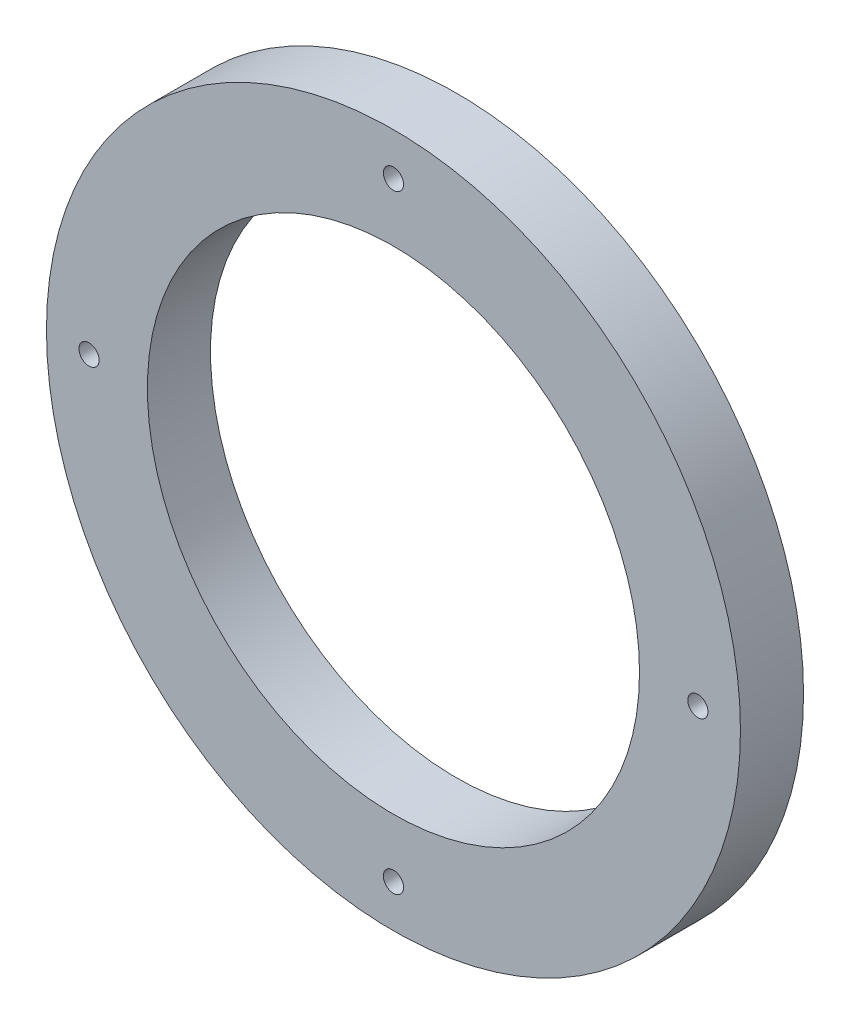
SolidWorks part; units mm, degrees
material "Custom Plastic"
ref_plane "Front Plane" through (0, 0, 0) normal (0, 0, 1) x (1, 0, 0)
ref_plane "Top Plane" through (0, 0, 0) normal (0, 1, 0) x (1, 0, 0)
ref_plane "Right Plane" through (0, 0, 0) normal (1, 0, 0) x (0, 0, -1)
sketch "Sketch1" plane through (0, 0, 0) normal (0, 0, 1) x (1, 0, 0)
  circle A0 centre (0, 0) radius 55
  circle A1 centre (0, 0) radius 39
  circle A2 centre (0, 48.25) radius 1.6
  circle A6 centre (48.25, 0) radius 1.6
  circle A7 centre (0, -48.25) radius 1.6
  circle A8 centre (-48.25, 0) radius 1.6
  point P15 (-1.5625, 1.5625)
  point P16 (0, 0)
  dimension "D1" = 110
  dimension "D2" = 78
  dimension "D3" = 3.2
  dimension "D4" = 48.25
  dimension "D5" = 4
extrude "Boss-Extrude1" add sketch "Sketch1" along normal blind 10
